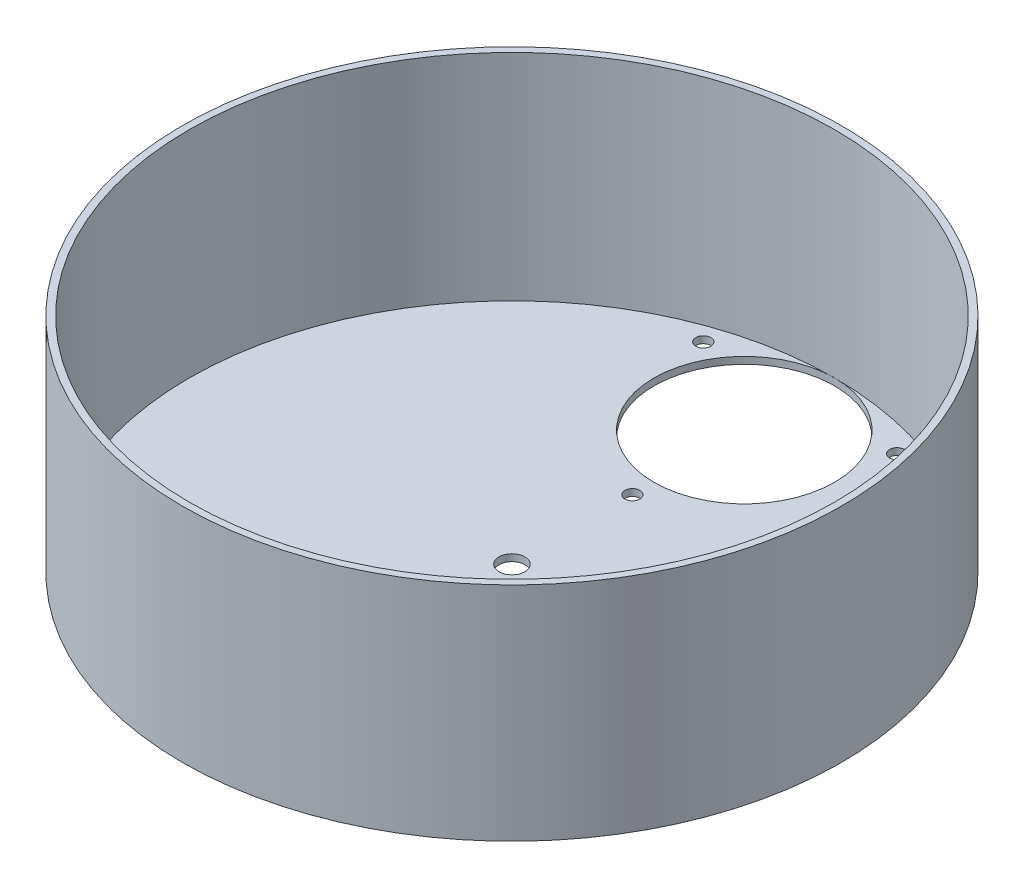
SolidWorks part; units mm, degrees
ref_plane "Front Plane" through (0, 0, 0) normal (0, 0, 1) x (1, 0, 0)
ref_plane "Top Plane" through (0, 0, 0) normal (0, 1, 0) x (1, 0, 0)
ref_plane "Right Plane" through (0, 0, 0) normal (1, 0, 0) x (0, 0, -1)
sketch "Sketch1" plane through (0, 0, 0) normal (0, 1, 0) x (1, 0, 0)
  circle A0 centre (0, 0) radius 75
  dimension "D1" = 150
extrude "Boss-Extrude1" add sketch "Sketch1" along normal blind 50
shell "Shell1" thickness 1.6
sketch "Sketch2" plane through (0, 0, 0) normal (0, 1, 0) x (1, 0, 0)
  circle A0 centre (0, 54) radius 21
  circle A1 centre (0, 0) radius 75 construction
  circle A2 centre (0, 0) radius 75 construction
  dimension "D1" = 42
  dimension "D2" = 54
extrude "Cut-Extrude1" cut sketch "Sketch2" against normal blind 50
sketch "Sketch3" plane through (0, 0, 0) normal (0, 1, 0) x (1, 0, 0)
  line L0 (0, 54) -> (0, 28) construction
  circle A0 centre (0, 28) radius 1.75
  circle A1 centre (-22.5167, 67) radius 1.75
  circle A2 centre (22.5167, 67) radius 1.75
  point P12 (0, 54)
  dimension "D2" = 3
  dimension "D1" = 26
extrude "Cut-Extrude2" cut sketch "Sketch3" against normal blind 50
sketch "Sketch4" plane through (0, 0, 0) normal (0, 1, 0) x (1, 0, 0)
  circle A0 centre (0, 0) radius 3
extrude "Cut-Extrude3" cut sketch "Sketch4" against normal blind 50
